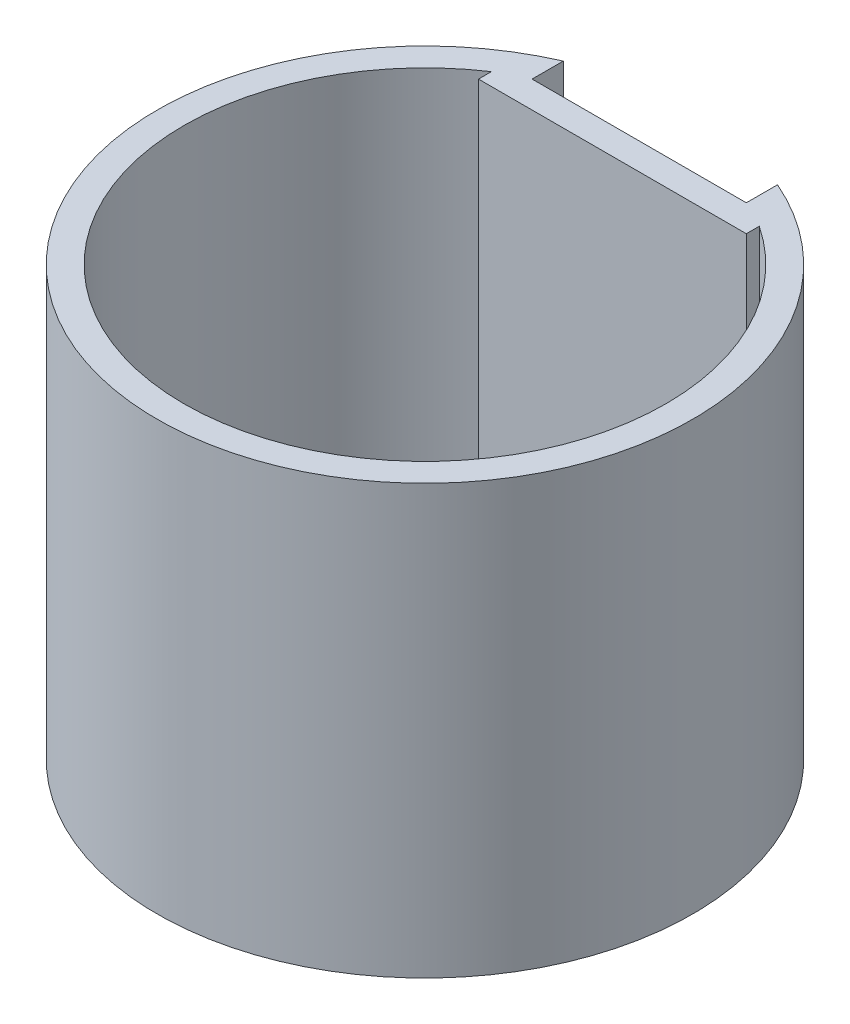
SolidWorks part; units mm, degrees
ref_plane "Front Plane" through (0, 0, 0) normal (0, 0, 1) x (1, 0, 0)
ref_plane "Top Plane" through (0, 0, 0) normal (0, 1, 0) x (1, 0, 0)
ref_plane "Right Plane" through (0, 0, 0) normal (1, 0, 0) x (0, 0, -1)
sketch "Sketch1" plane through (0, 0, 0) normal (0, 1, 0) x (1, 0, 0)
  line L0 (0, 96.0763) -> (0, -90.9844) construction
  line L1 (-126.2257, 80) -> (113.63, 80) construction
  line L2 (-40, 80) -> (40, 80)
  line L3 (40, 80) -> (40, 91.6515)
  line L4 (-40, 80) -> (-40, 91.6515)
  arc A0 (-40, 91.6515) -> (40, 91.6515) centre (0, 0) ccw
  point P9 (0, 80)
  dimension "D1" = 200
  dimension "D2" = 80
  dimension "D3" = 80
extrude "Boss-Extrude2" add sketch "Sketch1" against normal blind 160 contours L2 L3 A0 L4
sketch "Sketch2" plane through (0, 0, 0) normal (0, 1, 0) x (1, 0, 0)
  line L0 (-111.7258, 70) -> (129.5913, 70) construction
  line L1 (-50, 74.8331) -> (-50, 70)
  line L2 (-50, 70) -> (50, 70)
  line L3 (50, 70) -> (50, 74.8331)
  arc A0 (-50, 74.8331) -> (50, 74.8331) centre (0, 0) ccw
  point P7 (0, 70)
  dimension "D1" = 180
  dimension "D2" = 70
  dimension "D3" = 100
extrude "Cut-Extrude1" cut sketch "Sketch2" against normal blind 150 contours L2 L3 A0 L1
sketch "Sketch3" plane through (0, 0, -80) normal (0, 0, -1) x (-1, 0, 0)
  line L0 (40, -160) -> (-40, -160) construction
  line L1 (-40, -160) -> (-40, 0) construction
  circle A0 centre (0, -120) radius 7.5
  dimension "D1" = 15
  dimension "D2" = 40
  dimension "D3" = 40
extrude "Cut-Extrude2" cut sketch "Sketch3" against normal blind 10 from surface at 0 contours A0 starting at face at (0, -80, -80)
